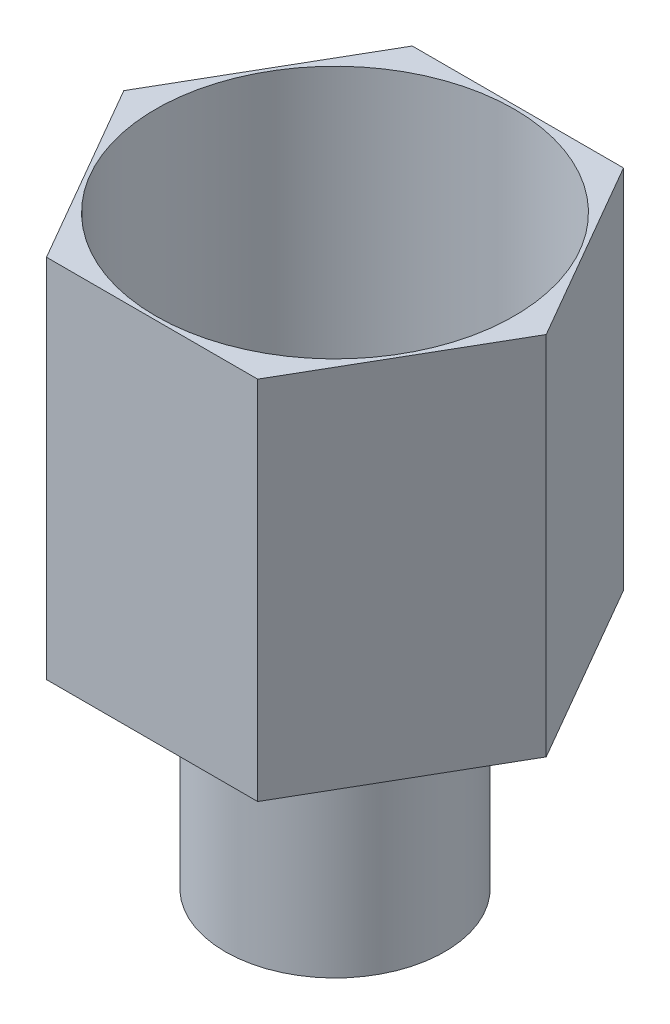
SolidWorks part; units mm, degrees
ref_plane "Front Plane" through (0, 0, 0) normal (0, 0, 1) x (1, 0, 0)
ref_plane "Top Plane" through (0, 0, 0) normal (0, 1, 0) x (1, 0, 0)
ref_plane "Right Plane" through (0, 0, 0) normal (1, 0, 0) x (0, 0, -1)
sketch "Sketch1" plane through (0, 0, 0) normal (0, 1, 0) x (1, 0, 0)
  line L1 (1.4434, -2.5) -> (2.8868, 0)
  line L2 (2.8868, 0) -> (1.4434, 2.5)
  line L3 (1.4434, 2.5) -> (-1.4434, 2.5)
  line L4 (-1.4434, 2.5) -> (-2.8868, 0)
  line L5 (-2.8868, 0) -> (-1.4434, -2.5)
  line L6 (-1.4434, -2.5) -> (1.4434, -2.5)
  circle A0 centre (0, 0) radius 2.5 construction
  dimension "D1" = 5
extrude "Boss-Extrude1" add sketch "Sketch1" along normal blind 5
sketch "Sketch2" plane through (0, 0, 0) normal (0, 1, 0) x (1, 0, 0)
  circle A0 centre (0, 0) radius 2.45
  dimension "D1" = 4.9
extrude "Cut-Extrude1" cut sketch "Sketch2" against normal blind 4 from surface at 5 starting at face at (0, 5, 0)
sketch "Sketch3" plane through (0, 0, 0) normal (0, 1, 0) x (1, 0, 0)
  circle A0 centre (0, 0) radius 1.5
  dimension "D1" = 3
extrude "Boss-Extrude2" add sketch "Sketch3" against normal blind 3
